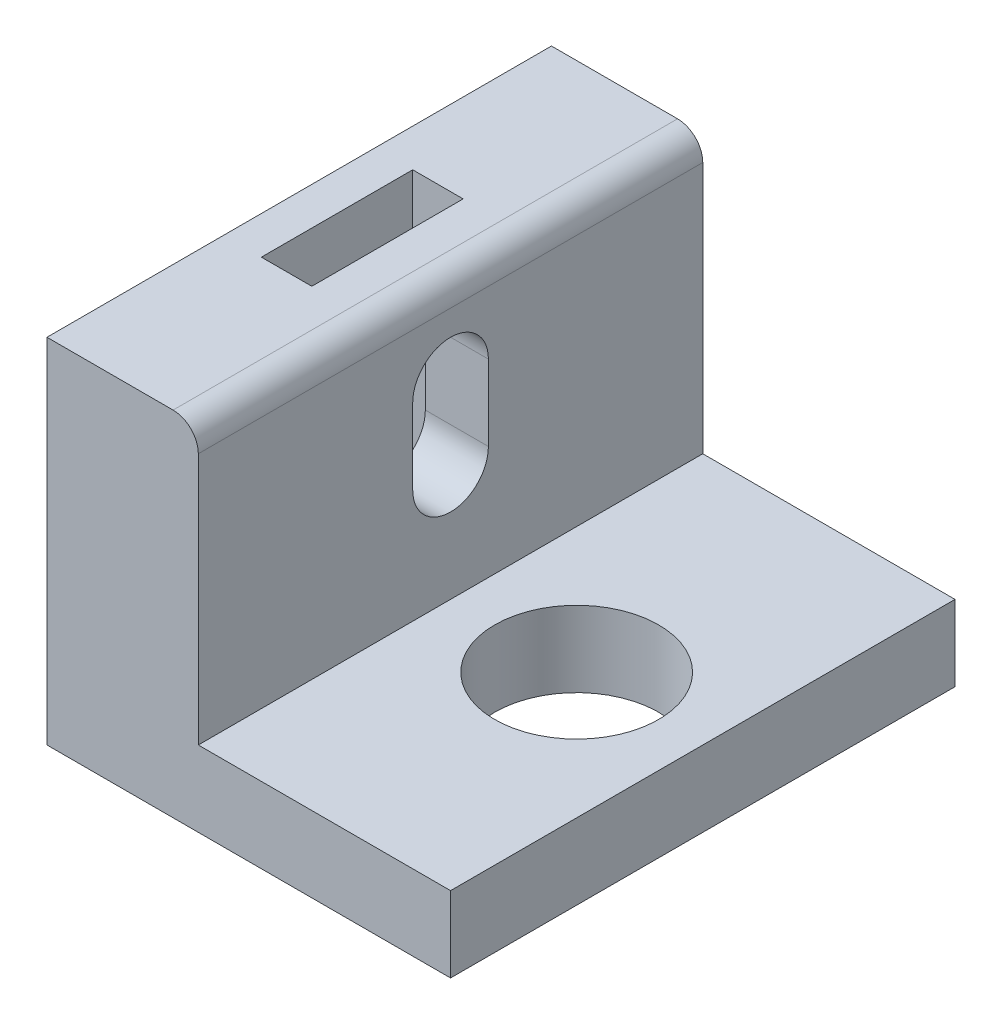
SolidWorks part; units mm, degrees
ref_plane "Piano frontale" through (0, 0, 0) normal (0, 0, 1) x (1, 0, 0)
ref_plane "Piano superiore" through (0, 0, 0) normal (0, 1, 0) x (1, 0, 0)
ref_plane "Piano destro" through (0, 0, 0) normal (1, 0, 0) x (0, 0, -1)
sketch "Schizzo2" plane through (0, 0, 0) normal (0, 0, 1) x (1, 0, 0)
  line L0 (0, 0) -> (0, 12.9875) construction
  line L1 (-4, 9.5) -> (-11, 9.5)
  line L2 (-11, 9.5) -> (-11, 23.5)
  line L3 (-11, 23.5) -> (-6, 23.5)
  line L4 (-5, 22.5) -> (-5, 12.5)
  line L5 (-5, 12.5) -> (4, 12.5)
  line L6 (4, 12.5) -> (4, 9.5)
  line L13 (-4, 0) -> (4, 0)
  line L14 (-7.5, 4) -> (-4, 0)
  line L15 (-7.5, 6.5) -> (-7.5, 4)
  line L16 (-4, 6.5) -> (-7.5, 6.5)
  line L17 (-4, 9.5) -> (-4, 6.5)
  line L44 (7.5, 4) -> (4, 0)
  line L45 (7.5, 6.5) -> (7.5, 4)
  line L46 (4, 6.5) -> (7.5, 6.5)
  line L72 (4, 9.5) -> (4, 6.5)
  arc A0 (-6, 23.5) -> (-5, 22.5) centre (-6, 22.5) cw
  point P9 (-5, 23.5)
  dimension "D11" = 1
  dimension "D1" = 8
  dimension "D2" = 4
  dimension "D3" = 2.5
  dimension "D4" = 8
  dimension "D5" = 3
  dimension "D6" = 15
  dimension "D7" = 11
  dimension "D8" = 6
  dimension "D9" = 3
  dimension "D10" = 14
extrude "Estrusione-Estrusione1" add sketch "Schizzo2" against normal blind 20
sketch "Schizzo6" plane through (-11, 0, 0) normal (-1, 0, 0) x (0, 0, 1)
  line L0 (0, 23.5) -> (0, 9.5) construction
  line L1 (-20, 23.5) -> (0, 23.5) construction
  line L2 (-10, 20) -> (-10, 17) construction
  line L3 (-8.5, 20) -> (-8.5, 17)
  line L4 (-11.5, 20) -> (-11.5, 17)
  line L5 (-20, 9.5) -> (0, 9.5) construction
  arc A1 (-8.5, 20) -> (-11.5, 20) centre (-10, 20) ccw
  arc A2 (-11.5, 17) -> (-8.5, 17) centre (-10, 17) ccw
  point P6 (-10, 18.5)
  dimension "D2" = 1.5
  dimension "D1" = 10
  dimension "D3" = 3.5
  dimension "D4" = 3
  dimension "D5" = 9
extrude "Taglio-Estrusione1" cut sketch "Schizzo6" against normal up to next
sketch "Schizzo11" plane through (0, 0, -20) normal (0, 0, -1) x (-1, 0, 0)
  line L0 (4, 0) -> (-4, 0) construction
  line L1 (7.5, 6.5) -> (7.5, 4) construction
  text T0 "3" font "Century Gothic" height 6.5
  dimension "D1" = 1
  dimension "D2" = 10.5
extrude "Estrusione-Estrusione4" add sketch "Schizzo11" along normal blind 0.6
sketch "Schizzo12" plane through (0, 23.5, 0) normal (0, 1, 0) x (1, 0, 0)
  line L0 (-6, 10) -> (-11, 10) construction
  line L1 (-6, 20) -> (-6, 0) construction
  line L2 (-11, 20) -> (-11, 0) construction
  line L4 (-7.5, 7) -> (-9.5, 7)
  line L5 (-7.5, 7) -> (-7.5, 13)
  line L6 (-7.5, 13) -> (-9.5, 13)
  line L7 (-9.5, 7) -> (-9.5, 13)
  line L8 (-7.5, 7) -> (-9.5, 13) construction
  line L9 (-7.5, 13) -> (-9.5, 7) construction
  point P6 (-8.5, 10)
  dimension "D1" = 2
  dimension "D2" = 6
extrude "Taglio-Estrusione2" cut sketch "Schizzo12" against normal blind 11
sketch "Schizzo13" plane through (0, 12.5, 0) normal (0, 1, 0) x (1, 0, 0)
  line L0 (0, 11.8665) -> (0, 9.0387) construction
  line L1 (0.9783, 10) -> (-1.6937, 10) construction
  line L2 (4, 20) -> (-5, 20) construction
  line L3 (4, 0) -> (-5, 0) construction
  line L7 (-5, 20) -> (-5, 0) construction
  circle A0 centre (0, 10) radius 3.25
  dimension "D1" = 6.5
  dimension "D2" = 5
extrude "Taglio-Estrusione3" cut sketch "Schizzo13" against normal through all
sketch "Schizzo14" plane through (0, 0, -20) normal (0, 0, -1) x (-1, 0, 0)
  line L0 (11, 9.5) -> (4, 9.5) construction
  line L1 (11, 9.5) -> (-7.5, 9.5)
  line L2 (11, 9.5) -> (11, 0)
  line L3 (11, 0) -> (-7.5, 0)
  line L4 (-7.5, 9.5) -> (-7.5, 0)
  line L5 (11, 9.5) -> (-7.5, 0) construction
  line L6 (11, 0) -> (-7.5, 9.5) construction
  line L7 (4, 0) -> (-4, 0) construction
  line L8 (11, 23.5) -> (11, 9.5) construction
  line L9 (-7.5, 4) -> (-7.5, 6.5) construction
extrude "Taglio-Estrusione4" cut sketch "Schizzo14" against normal up to next and the other way up to next
sketch "Schizzo15" plane through (0, 12.5, 0) normal (0, 1, 0) x (1, 0, 0)
  line L0 (4, 20) -> (-5, 20) construction
  line L1 (5, 20) -> (4, 20)
  line L2 (5, 20) -> (5, 0)
  line L3 (5, 0) -> (4, 0)
  line L4 (4, 20) -> (4, 0)
  line L5 (5, 20) -> (4, 0) construction
  line L6 (5, 0) -> (4, 20) construction
  circle A0 centre (0, 10) radius 3.25 construction
  point P0 (4.5, 10)
  dimension "D1" = 5
extrude "Estrusione-Estrusione5" add sketch "Schizzo15" against normal through all
